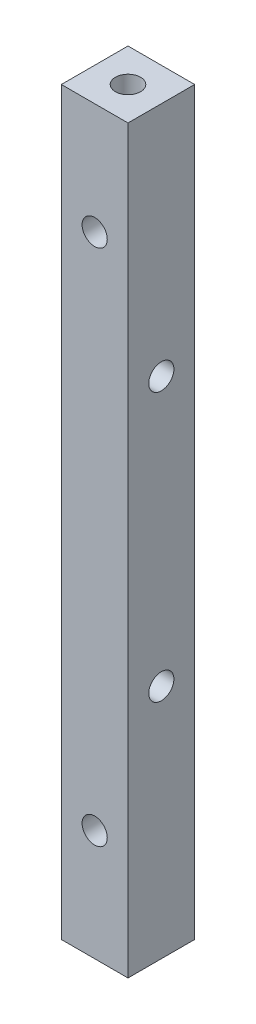
SolidWorks part; units mm, degrees
material "6061-T6 (SS)"
ref_plane "Front Plane" through (0, 0, 0) normal (0, 0, 1) x (1, 0, 0)
ref_plane "Top Plane" through (0, 0, 0) normal (0, 1, 0) x (1, 0, 0)
ref_plane "Right Plane" through (0, 0, 0) normal (1, 0, 0) x (0, 0, -1)
sketch "Sketch1" plane through (0, 0, 0) normal (0, 1, 0) x (1, 0, 0)
  line L1 (-4.572, 4.572) -> (4.572, 4.572)
  line L2 (-4.572, 4.572) -> (-4.572, -4.572)
  line L3 (-4.572, -4.572) -> (4.572, -4.572)
  line L4 (4.572, 4.572) -> (4.572, -4.572)
  line L5 (-4.572, 4.572) -> (4.572, -4.572) construction
  line L6 (-4.572, -4.572) -> (4.572, 4.572) construction
  point P0 (0, 0)
  dimension "D1" = 9.144
extrude "Boss-Extrude1" add sketch "Sketch1" along normal blind 101.6
sketch "Sketch3" plane through (0, 0, 4.572) normal (0, 0, 1) x (1, 0, 0)
  line L0 (0, 86.36) -> (0, 15.24) construction
  line L1 (4.572, 101.6) -> (4.572, 0) construction
  line L2 (-4.572, 0) -> (4.572, 0) construction
  line L3 (-4.572, 101.6) -> (4.572, 101.6) construction
  point P3 (0, 50.8)
  point P8 (4.572, 50.8)
  dimension "D1" = 15.24
  dimension "D2" = 15.24
hole_wizard "Tap Drill for #8-32 Tap1" positions "Sketch4" profile "Sketch6" hole size "#8-32" standard "ANSI Inch" end condition through all
sketch "Sketch4" plane through (0, 0, 4.572) normal (0, 0, 1) x (1, 0, 0)
  point P0 (0, 86.36)
  point P3 (0, 15.24)
sketch "Sketch6" plane through (0, 86.36, 4.572) normal (1, 0, 0) x (0, -1, 0)
  line L0 (0, 0) -> (0, 9.144)
  line L1 (0, 9.144) -> (1.7272, 9.144)
  line L2 (1.7272, 9.144) -> (1.7272, 0)
  line L5 (1.7272, 0) -> (0, 0)
  line L11 (0, -6.35) -> (0, 107.95) construction
  dimension "Thru Hole Dia." = 3.4544
  dimension "Thru Hole Depth" = 9.144
sketch "Sketch7" plane through (4.572, 0, 0) normal (1, 0, 0) x (0, 0, -1)
  line L0 (0, 69.215) -> (0, 32.385) construction
  line L2 (-4.572, 0) -> (4.572, 0) construction
  point P3 (0, 50.8)
  point P8 (0, 0)
  dimension "D1" = 36.83
hole_wizard "Tap Drill for #8-32 Tap2" positions "Sketch10" profile "Sketch11" hole size "#8-32" standard "ANSI Inch" end condition through all
sketch "Sketch10" plane through (4.572, 0, 0) normal (1, 0, 0) x (0, 0, -1)
  point P0 (0, 69.215)
  point P3 (0, 32.385)
sketch "Sketch11" plane through (4.572, 69.215, 0) normal (0, 1, 0) x (0, 0, -1)
  line L0 (0, 0) -> (0, 9.144)
  line L1 (0, 9.144) -> (1.7272, 9.144)
  line L2 (1.7272, 9.144) -> (1.7272, 0)
  line L5 (1.7272, 0) -> (0, 0)
  line L11 (0, -6.35) -> (0, 107.95) construction
  dimension "Thru Hole Dia." = 3.4544
  dimension "Thru Hole Depth" = 9.144
hole_wizard "Tap Drill for #8-32 Tap3" positions "Sketch13" profile "Sketch15" hole size "#8-32" standard "ANSI Inch"
sketch "Sketch13" plane through (0, 101.6, 0) normal (0, 1, 0) x (1, 0, 0)
  point P0 (0, 0)
sketch "Sketch15" plane through (0, 101.6, 0) normal (1, 0, 0) x (0, 0, 1)
  line L0 (0, 0) -> (0, 8.6578)
  line L1 (0, 8.6578) -> (1.7272, 7.62)
  line L2 (1.7272, 7.62) -> (1.7272, 0)
  line L5 (1.7272, 0) -> (0, 0)
  line L10 (0, 8.6578) -> (-1.7272, 7.62) construction
  line L11 (0, -6.35) -> (0, 107.95) construction
  dimension "Hole Dia." = 3.4544
  dimension "Hole Depth" = 7.62
  dimension "Drill Angle" = 118
